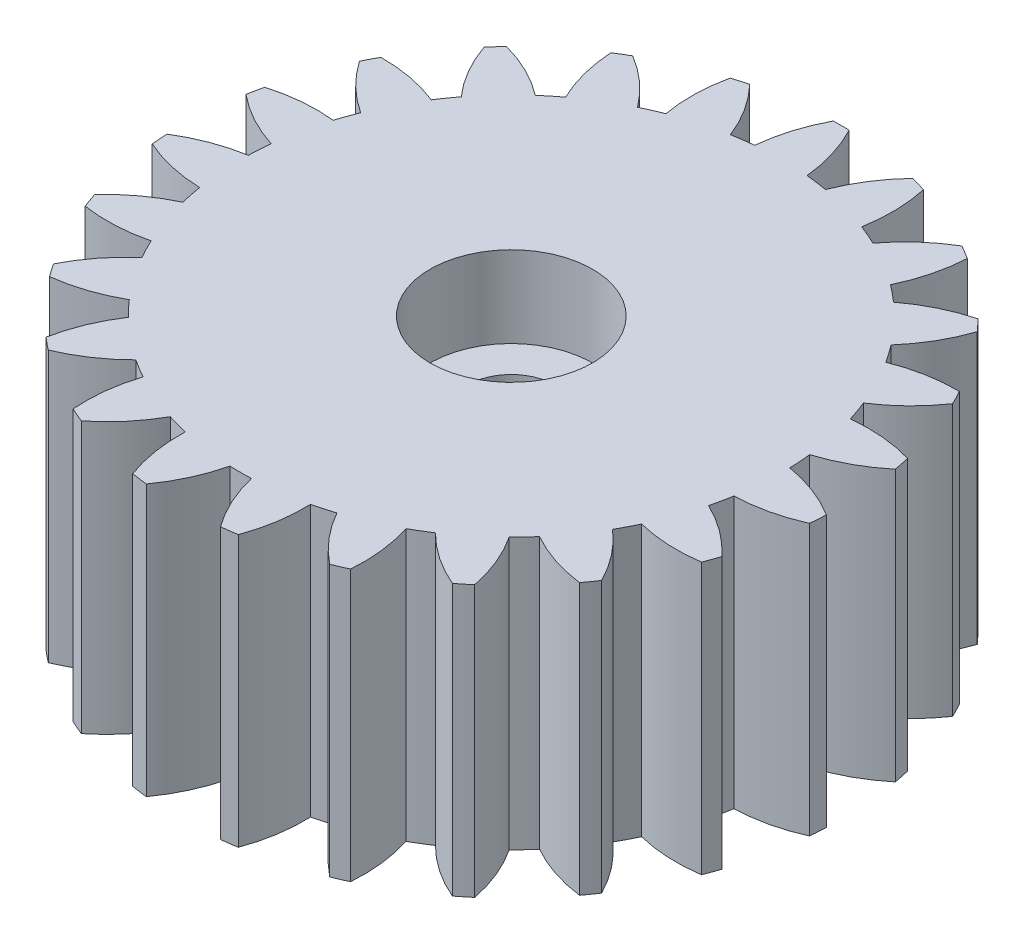
SolidWorks part; units mm, degrees
ref_plane "Front" through (0, 0, 0) normal (0, 0, 1) x (1, 0, 0)
ref_plane "Top" through (0, 0, 0) normal (0, 1, 0) x (1, 0, 0)
ref_plane "Right" through (0, 0, 0) normal (1, 0, 0) x (0, 0, -1)
sketch "Sketch1" plane through (0, 0, 0) normal (0, 1, 0) x (1, 0, 0)
  circle A0 centre (0, 0) radius 10
  dimension "D1" = 20
extrude "Boss-Extrude1" add sketch "Sketch1" along normal blind 10
sketch "Sketch3" plane through (0, 10, 0) normal (0, 1, 0) x (1, 0, 0)
  arc A0 (-0.2927, 12.1828) -> (-0.9725, 9.9) centre (5.0034, 9.3629) ccw
  arc A1 (0.9725, 9.9) -> (0.2927, 12.1828) centre (-5.0034, 9.3629) ccw
  arc A2 (0.2927, 12.1828) -> (-0.2927, 12.1828) centre (0, 0) ccw
  arc A3 (-0.9725, 9.9) -> (0.9725, 9.9) centre (0, 0) cw
  arc A4 (3.0051, 11.8099) -> (1.7346, 9.7953) centre (7.344, 7.6658) ccw
  arc A5 (3.6074, 9.2705) -> (3.5687, 11.652) centre (-2.2918, 10.3656) ccw
  arc A6 (3.5687, 11.652) -> (3.0051, 11.8099) centre (0, 0) ccw
  arc A7 (1.7346, 9.7953) -> (3.6074, 9.2705) centre (0, 0) cw
  arc A8 (6.0799, 10.5612) -> (4.313, 8.964) centre (9.1398, 5.4002) ccw
  arc A9 (5.9748, 7.9535) -> (6.58, 10.2571) centre (0.5898, 10.5995) ccw
  arc A10 (6.58, 10.2571) -> (6.0799, 10.5612) centre (0, 0) ccw
  arc A11 (4.313, 8.964) -> (5.9748, 7.9535) centre (0, 0) cw
  arc A12 (8.7038, 8.5293) -> (6.5715, 7.468) centre (10.2579, 2.734) ccw
  arc A13 (7.8991, 6.0465) -> (9.1034, 8.1015) centre (3.4276, 10.0474) ccw
  arc A14 (9.1034, 8.1015) -> (8.7038, 8.5293) centre (0, 0) ccw
  arc A15 (6.5715, 7.468) -> (7.8991, 6.0465) centre (0, 0) cw
  arc A16 (10.6823, 5.8647) -> (8.3427, 5.4181) centre (10.6151, -0.1349) ccw
  arc A17 (9.2375, 3.6912) -> (10.9515, 5.345) centre (6.0113, 8.75) ccw
  arc A18 (10.9515, 5.345) -> (10.6823, 5.8647) centre (0, 0) ccw
  arc A19 (8.3427, 5.4181) -> (9.2375, 3.6912) centre (0, 0) cw
  arc A20 (11.8684, 2.7652) -> (9.4951, 2.9664) centre (10.1851, -2.9938) ccw
  arc A21 (9.8908, 1.0621) -> (11.9875, 2.1921) centre (8.1491, 6.8037) ccw
  arc A22 (11.9875, 2.1921) -> (11.8684, 2.7652) centre (0, 0) ccw
  arc A23 (9.4951, 2.9664) -> (9.8908, 1.0621) centre (0, 0) cw
  arc A24 (12.1743, -0.5394) -> (9.9433, 0.2946) centre (8.9996, -5.6307) ccw
  arc A25 (9.8106, -1.6458) -> (12.1344, -1.1234) centre (9.6825, 4.3528) ccw
  arc A26 (12.1344, -1.1234) -> (12.1743, -0.5394) centre (0, 0) ccw
  arc A27 (9.9433, 0.2946) -> (9.8106, -1.6458) centre (0, 0) cw
  arc A28 (11.5773, -3.804) -> (9.654, -2.399) centre (7.1468, -7.85) ccw
  arc A29 (9.0027, -4.2316) -> (11.3813, -4.3555) centre (10.4978, 1.5791) ccw
  arc A30 (11.3813, -4.3555) -> (11.5773, -3.804) centre (0, 0) ccw
  arc A31 (9.654, -2.399) -> (9.0027, -4.2316) centre (0, 0) cw
  arc A32 (10.1217, -6.7865) -> (8.6488, -4.9146) centre (4.7638, -9.4871) ccw
  arc A33 (7.5272, -6.5036) -> (9.7842, -7.2646) centre (10.5346, -1.3118) ccw
  arc A34 (9.7842, -7.2646) -> (10.1217, -6.7865) centre (0, 0) ccw
  arc A35 (8.6488, -4.9146) -> (7.5272, -6.5036) centre (0, 0) cw
  arc A36 (7.9154, -9.2656) -> (7.0021, -7.0658) centre (2.0276, -10.4205) ccw
  arc A37 (5.4934, -8.2933) -> (7.4614, -9.635) centre (9.79, -4.1053) ccw
  arc A38 (7.4614, -9.635) -> (7.9154, -9.2656) centre (0, 0) ccw
  arc A39 (7.0021, -7.0658) -> (5.4934, -8.2933) centre (0, 0) cw
  arc A40 (5.122, -11.0576) -> (4.8361, -8.693) centre (-0.859, -10.5811) ccw
  arc A41 (3.0522, -9.4678) -> (4.5852, -11.2908) centre (8.3194, -6.5944) ccw
  arc A42 (4.5852, -11.2908) -> (5.122, -11.0576) centre (0, 0) ccw
  arc A43 (4.8361, -8.693) -> (3.0522, -9.4678) centre (0, 0) cw
  arc A44 (1.9488, -12.0294) -> (2.3115, -9.6754) centre (-3.6819, -9.957) ccw
  arc A45 (0.3846, -9.9402) -> (1.369, -12.1091) centre (6.2317, -8.5944) ccw
  arc A46 (1.369, -12.1091) -> (1.9488, -12.0294) centre (0, 0) ccw
  arc A47 (2.3115, -9.6754) -> (0.3846, -9.9402) centre (0, 0) cw
  arc A48 (-1.369, -12.1091) -> (-0.3846, -9.9402) centre (-6.2317, -8.5944) ccw
  arc A49 (-2.3115, -9.6754) -> (-1.9488, -12.0294) centre (3.6819, -9.957) ccw
  arc A50 (-1.9488, -12.0294) -> (-1.369, -12.1091) centre (0, 0) ccw
  arc A51 (-0.3846, -9.9402) -> (-2.3115, -9.6754) centre (0, 0) cw
  arc A52 (-4.5852, -11.2908) -> (-3.0522, -9.4678) centre (-8.3194, -6.5944) ccw
  arc A53 (-4.8361, -8.693) -> (-5.122, -11.0576) centre (0.859, -10.5811) ccw
  arc A54 (-5.122, -11.0576) -> (-4.5852, -11.2908) centre (0, 0) ccw
  arc A55 (-3.0522, -9.4678) -> (-4.8361, -8.693) centre (0, 0) cw
  arc A56 (-7.4614, -9.635) -> (-5.4934, -8.2933) centre (-9.79, -4.1053) ccw
  arc A57 (-7.0021, -7.0658) -> (-7.9154, -9.2656) centre (-2.0276, -10.4205) ccw
  arc A58 (-7.9154, -9.2656) -> (-7.4614, -9.635) centre (0, 0) ccw
  arc A59 (-5.4934, -8.2933) -> (-7.0021, -7.0658) centre (0, 0) cw
  arc A60 (-9.7842, -7.2646) -> (-7.5272, -6.5036) centre (-10.5346, -1.3118) ccw
  arc A61 (-8.6488, -4.9146) -> (-10.1217, -6.7865) centre (-4.7638, -9.4871) ccw
  arc A62 (-10.1217, -6.7865) -> (-9.7842, -7.2646) centre (0, 0) ccw
  arc A63 (-7.5272, -6.5036) -> (-8.6488, -4.9146) centre (0, 0) cw
  arc A64 (-11.3813, -4.3555) -> (-9.0027, -4.2316) centre (-10.4978, 1.5791) ccw
  arc A65 (-9.654, -2.399) -> (-11.5773, -3.804) centre (-7.1468, -7.85) ccw
  arc A66 (-11.5773, -3.804) -> (-11.3813, -4.3555) centre (0, 0) ccw
  arc A67 (-9.0027, -4.2316) -> (-9.654, -2.399) centre (0, 0) cw
  arc A68 (-12.1344, -1.1234) -> (-9.8106, -1.6458) centre (-9.6825, 4.3528) ccw
  arc A69 (-9.9433, 0.2946) -> (-12.1743, -0.5394) centre (-8.9996, -5.6307) ccw
  arc A70 (-12.1743, -0.5394) -> (-12.1344, -1.1234) centre (0, 0) ccw
  arc A71 (-9.8106, -1.6458) -> (-9.9433, 0.2946) centre (0, 0) cw
  arc A72 (-11.9875, 2.1921) -> (-9.8908, 1.0621) centre (-8.1491, 6.8037) ccw
  arc A73 (-9.4951, 2.9664) -> (-11.8684, 2.7652) centre (-10.1851, -2.9938) ccw
  arc A74 (-11.8684, 2.7652) -> (-11.9875, 2.1921) centre (0, 0) ccw
  arc A75 (-9.8908, 1.0621) -> (-9.4951, 2.9664) centre (0, 0) cw
  arc A76 (-10.9515, 5.345) -> (-9.2375, 3.6912) centre (-6.0113, 8.75) ccw
  arc A77 (-8.3427, 5.4181) -> (-10.6823, 5.8647) centre (-10.6151, -0.1349) ccw
  arc A78 (-10.6823, 5.8647) -> (-10.9515, 5.345) centre (0, 0) ccw
  arc A79 (-9.2375, 3.6912) -> (-8.3427, 5.4181) centre (0, 0) cw
  arc A80 (-9.1034, 8.1015) -> (-7.8991, 6.0465) centre (-3.4276, 10.0474) ccw
  arc A81 (-6.5715, 7.468) -> (-8.7038, 8.5293) centre (-10.2579, 2.734) ccw
  arc A82 (-8.7038, 8.5293) -> (-9.1034, 8.1015) centre (0, 0) ccw
  arc A83 (-7.8991, 6.0465) -> (-6.5715, 7.468) centre (0, 0) cw
  arc A84 (-6.58, 10.2571) -> (-5.9748, 7.9535) centre (-0.5898, 10.5995) ccw
  arc A85 (-4.313, 8.964) -> (-6.0799, 10.5612) centre (-9.1398, 5.4002) ccw
  arc A86 (-6.0799, 10.5612) -> (-6.58, 10.2571) centre (0, 0) ccw
  arc A87 (-5.9748, 7.9535) -> (-4.313, 8.964) centre (0, 0) cw
  arc A88 (-3.5687, 11.652) -> (-3.6074, 9.2705) centre (2.2918, 10.3656) ccw
  arc A89 (-1.7346, 9.7953) -> (-3.0051, 11.8099) centre (-7.344, 7.6658) ccw
  arc A90 (-3.0051, 11.8099) -> (-3.5687, 11.652) centre (0, 0) ccw
  arc A91 (-3.6074, 9.2705) -> (-1.7346, 9.7953) centre (0, 0) cw
  point P63 (0, 0)
  dimension "D1" = 0.9725
  dimension "D2" = 0.9725
  dimension "D3" = 0.2927
  dimension "D4" = 0.2927
  dimension "D5" = 2.2828
  dimension "D6" = 9.9
  dimension "D7" = 23
extrude "Boss-Extrude2" add sketch "Sketch3" against normal blind 10
sketch "Sketch4" plane through (0, 0, 0) normal (0, -1, 0) x (1, 0, 0)
  circle A0 centre (0, 0) radius 2.825
  dimension "D1" = 5.65
extrude "Cut-Extrude1" cut sketch "Sketch4" against normal blind 3.7
sketch "Sketch5" plane through (0, 10, 0) normal (0, 1, 0) x (1, 0, 0)
  circle A0 centre (0, 0) radius 1.6
  dimension "D1" = 3.2
extrude "Cut-Extrude2" cut sketch "Sketch5" against normal through all
sketch "Sketch7" plane through (0, 10, 0) normal (0, 1, 0) x (1, 0, 0)
  circle A0 centre (0, 0) radius 3
  dimension "D1" = 6
extrude "Cut-Extrude3" cut sketch "Sketch7" against normal blind 3
